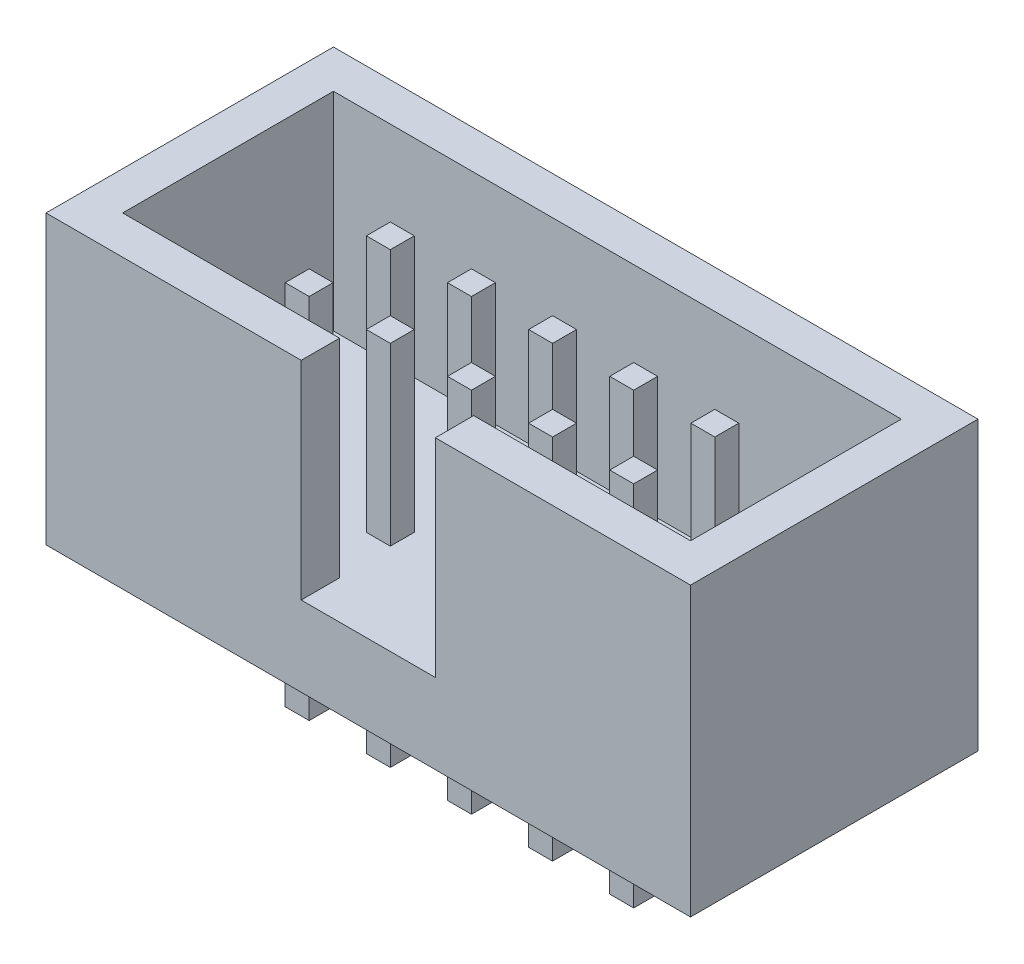
SolidWorks part; units mm, degrees
ref_plane "前视基准面" through (0, 0, 0) normal (0, 0, 1) x (1, 0, 0)
ref_plane "上视基准面" through (0, 0, 0) normal (0, 1, 0) x (1, 0, 0)
ref_plane "右视基准面" through (0, 0, 0) normal (1, 0, 0) x (0, 0, -1)
sketch "草图1" plane through (0, 0, 0) normal (0, 1, 0) x (1, 0, 0)
  line L0 (0, 85.0964) -> (0, -118.2031) construction
  line L1 (-10.09, 4.5) -> (10.09, 4.5)
  line L2 (-10.09, 4.5) -> (-10.09, -4.5)
  line L3 (-10.09, -4.5) -> (10.09, -4.5)
  line L4 (10.09, 4.5) -> (10.09, -4.5)
  line L5 (-200.5452, 0) -> (261.2352, 0) construction
  dimension "D1" = 9
  dimension "D2" = 20.18
extrude "拉伸1" add sketch "草图1" along normal blind 9
sketch "草图2" plane through (0, 9, 0) normal (0, 1, 0) x (-1, 0, 0)
  line L8 (-8.89, 3.3) -> (-8.89, -3.3)
  line L9 (8.89, 3.3) -> (-8.89, 3.3)
  line L10 (8.89, -3.3) -> (8.89, 3.3)
  line L11 (-8.89, -3.3) -> (8.89, -3.3)
  line L12 (-8.89, 3.3) -> (-8.89, -3.3)
  line L13 (8.89, 3.3) -> (-8.89, 3.3)
  line L14 (8.89, -3.3) -> (8.89, 3.3)
  line L15 (-8.89, -3.3) -> (8.89, -3.3)
  dimension "D1" = 1.2
extrude "切除-拉伸1" cut sketch "草图2" against normal blind 6.5
sketch "草图3" plane through (0, 0, 4.5) normal (0, 0, 1) x (1, 0, 0)
  line L0 (-10.09, 9) -> (10.09, 9) construction
  line L1 (-2.1, 9) -> (2.1, 9)
  line L2 (-2.1, 9) -> (-2.1, 2.5)
  line L3 (-2.1, 2.5) -> (2.1, 2.5)
  line L4 (2.1, 9) -> (2.1, 2.5)
  line L5 (-8.89, 2.5) -> (8.89, 2.5) construction
  line L6 (0, 9.4226) -> (0, -4.0288) construction
  dimension "D1" = 4.2
extrude "切除-拉伸2" cut sketch "草图3" against normal blind 6.5
sketch "草图5" plane through (0, 0, 0) normal (0, -1, 0) x (1, 0, 0)
  line L0 (0, 6.0683) -> (0, -6.9786) construction
  line L1 (-21.1981, 0) -> (21.4095, 0) construction
  line L2 (-2.4898, 1.27) -> (1.0953, 1.27) construction
  line L3 (-0.375, 0.895) -> (0.375, 0.895)
  line L4 (-0.375, 0.895) -> (-0.375, 1.645)
  line L5 (-0.375, 1.645) -> (0.375, 1.645)
  line L6 (0.375, 0.895) -> (0.375, 1.645)
  line L7 (2.165, 0.895) -> (2.915, 0.895)
  line L8 (2.165, 0.895) -> (2.165, 1.645)
  line L9 (2.165, 1.645) -> (2.915, 1.645)
  line L10 (2.915, 0.895) -> (2.915, 1.645)
  line L11 (4.705, 0.895) -> (5.455, 0.895)
  line L12 (4.705, 0.895) -> (4.705, 1.645)
  line L13 (4.705, 1.645) -> (5.455, 1.645)
  line L14 (5.455, 0.895) -> (5.455, 1.645)
  line L31 (-2.915, 0.895) -> (-2.165, 0.895)
  line L32 (-2.915, 0.895) -> (-2.915, 1.645)
  line L33 (-2.915, 1.645) -> (-2.165, 1.645)
  line L34 (-2.165, 0.895) -> (-2.165, 1.645)
  line L35 (-5.455, 0.895) -> (-4.705, 0.895)
  line L36 (-5.455, 0.895) -> (-5.455, 1.645)
  line L37 (-5.455, 1.645) -> (-4.705, 1.645)
  line L38 (-4.705, 0.895) -> (-4.705, 1.645)
  line L55 (-2.4898, -1.27) -> (1.0953, -1.27) construction
  line L72 (-4.705, -0.895) -> (-4.705, -1.645)
  line L73 (-5.455, -1.645) -> (-4.705, -1.645)
  line L74 (-5.455, -0.895) -> (-5.455, -1.645)
  line L75 (-5.455, -0.895) -> (-4.705, -0.895)
  line L76 (-2.165, -0.895) -> (-2.165, -1.645)
  line L77 (-2.915, -1.645) -> (-2.165, -1.645)
  line L78 (-2.915, -0.895) -> (-2.915, -1.645)
  line L79 (-2.915, -0.895) -> (-2.165, -0.895)
  line L96 (5.455, -0.895) -> (5.455, -1.645)
  line L97 (4.705, -1.645) -> (5.455, -1.645)
  line L98 (4.705, -0.895) -> (4.705, -1.645)
  line L99 (4.705, -0.895) -> (5.455, -0.895)
  line L100 (2.915, -0.895) -> (2.915, -1.645)
  line L101 (2.165, -1.645) -> (2.915, -1.645)
  line L102 (2.165, -0.895) -> (2.165, -1.645)
  line L103 (2.165, -0.895) -> (2.915, -0.895)
  line L104 (0.375, -0.895) -> (0.375, -1.645)
  line L105 (-0.375, -1.645) -> (0.375, -1.645)
  line L106 (-0.375, -0.895) -> (-0.375, -1.645)
  line L107 (-0.375, -0.895) -> (0.375, -0.895)
  line L108 (-7.995, 0.895) -> (-7.245, 0.895) [skipped]
  line L109 (-7.995, 0.895) -> (-7.995, 1.645) [skipped]
  line L110 (-7.995, 1.645) -> (-7.245, 1.645) [skipped]
  line L111 (-7.245, 0.895) -> (-7.245, 1.645) [skipped]
  line L112 (7.245, 0.895) -> (7.995, 0.895) [skipped]
  line L113 (7.245, 0.895) -> (7.245, 1.645) [skipped]
  line L114 (7.245, 1.645) -> (7.995, 1.645) [skipped]
  line L115 (7.995, 0.895) -> (7.995, 1.645) [skipped]
  dimension "D1" = 0.75
  dimension "D2" = 0.75
  dimension "D3" = 1.27
extrude "拉伸2" add sketch "草图5" along normal blind 3.5 and the other way offset from surface (8 mm away) 1 other way up to face at (0, 9, 1.3)
